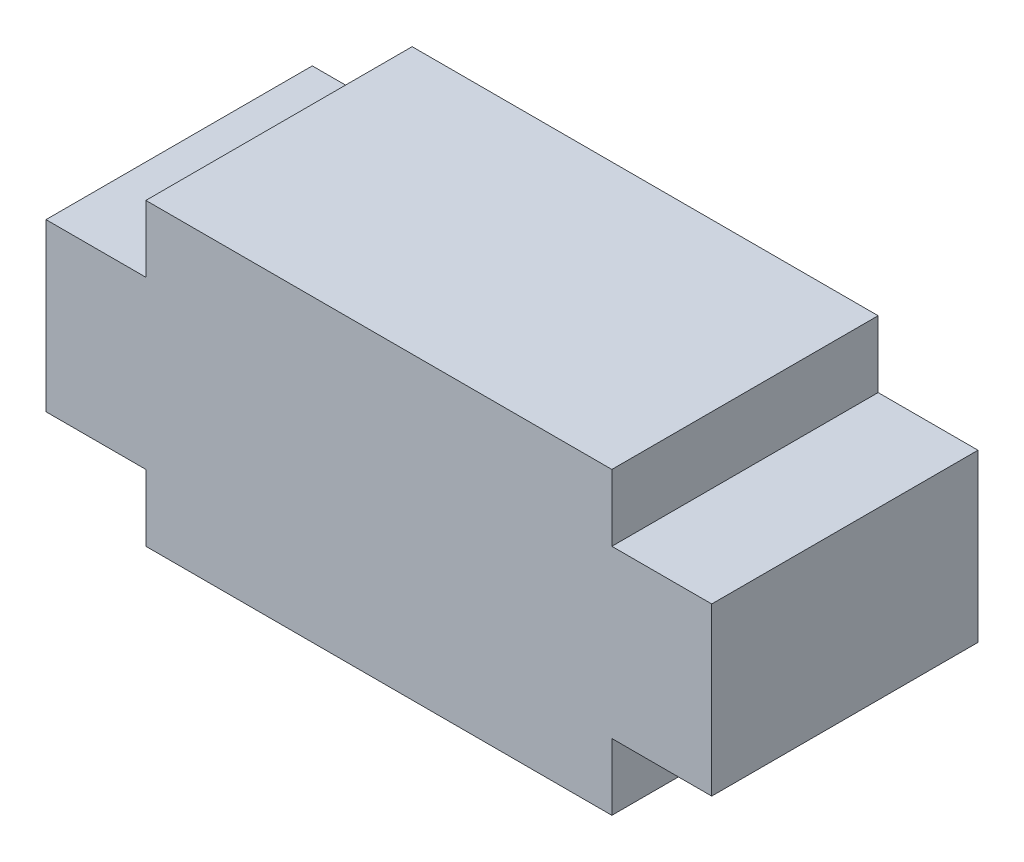
SolidWorks part; units mm, degrees
ref_plane "前视基准面" through (0, 0, 0) normal (0, 0, 1) x (1, 0, 0)
ref_plane "上视基准面" through (0, 0, 0) normal (0, 1, 0) x (1, 0, 0)
ref_plane "右视基准面" through (0, 0, 0) normal (1, 0, 0) x (0, 0, -1)
sketch "草图1" plane through (0, 0, 0) normal (0, 0, 1) x (1, 0, 0)
  line L0 (1, -0.25) -> (0.7, -0.25)
  line L1 (0.7, -0.25) -> (0.7, -0.45)
  line L2 (0.7, -0.45) -> (-0.7, -0.45)
  line L3 (-0.7, -0.45) -> (-0.7, -0.25)
  line L4 (-0.7, -0.25) -> (-1, -0.25)
  line L5 (-1, -0.25) -> (-1, 0.25)
  line L6 (-1, 0.25) -> (-0.7, 0.25)
  line L7 (-0.7, 0.25) -> (-0.7, 0.45)
  line L8 (-0.7, 0.45) -> (0.7, 0.45)
  line L9 (0.7, 0.45) -> (0.7, 0.25)
  line L10 (0.7, 0.25) -> (1, 0.25)
  line L11 (1, 0.25) -> (1, -0.25)
extrude "Component_Outline" add sketch "草图1" along normal blind 0.8 separate body
sketch3d "3D草图1"
  line L0 (0, 0, 0) -> (1, 0, 0)
  line L1 (0, 0, 0) -> (0, 1, 0)
  line L2 (0, 0, 0) -> (0, 0, 1)
  point P0 (0, 0, 0)
